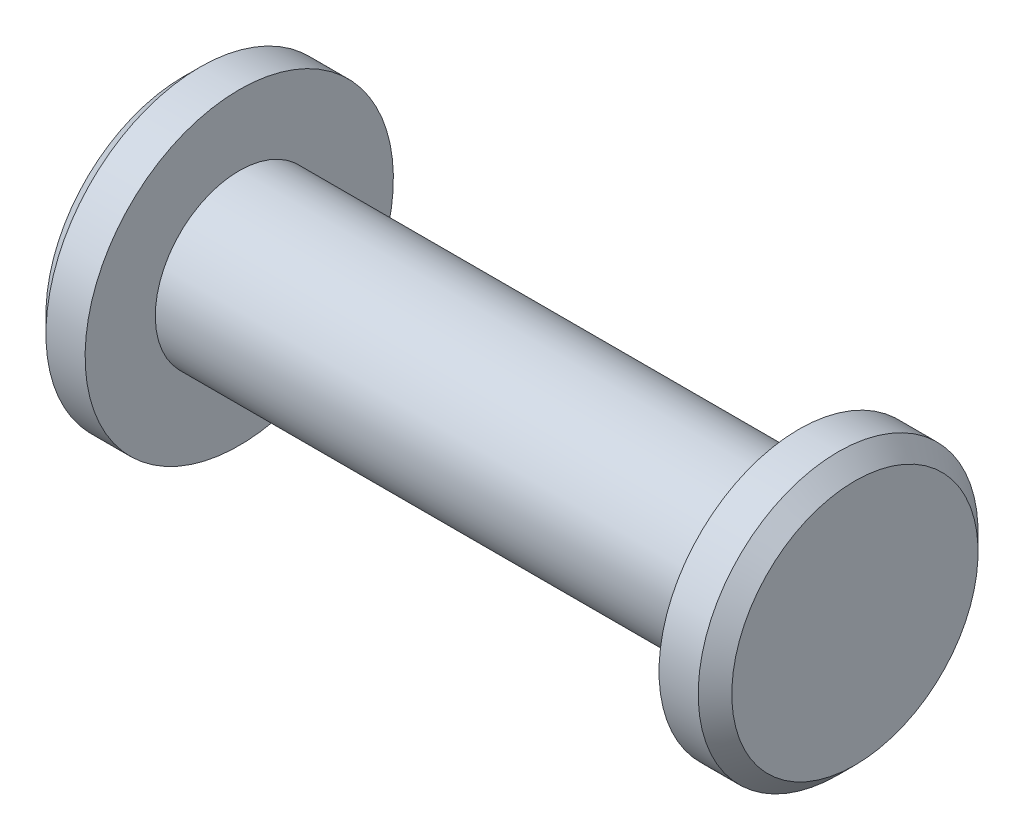
SolidWorks part; units mm, degrees
ref_plane "Front Plane" through (0, 0, 0) normal (0, 0, 1) x (1, 0, 0)
ref_plane "Top Plane" through (0, 0, 0) normal (0, 1, 0) x (1, 0, 0)
ref_plane "Right Plane" through (0, 0, 0) normal (1, 0, 0) x (0, 0, -1)
sketch "Sketch1" plane through (0, 0, 0) normal (0, 0, 1) x (1, 0, 0)
  line L0 (0, 0) -> (-120, 0)
  line L1 (-120, 0) -> (-120, 27.5382)
  line L2 (-120, 27.5382) -> (-110, 27.5382)
  line L3 (-110, 27.5382) -> (-110, 15)
  line L4 (-110, 15) -> (-10, 15)
  line L5 (-10, 15) -> (-10, 25)
  line L6 (-10, 25) -> (0, 25)
  line L7 (0, 25) -> (0, 0)
  dimension "D1" = 100
  dimension "D2" = 10
  dimension "D3" = 10
  dimension "D4" = 25
  dimension "D5" = 15
revolve "Revolve1" add sketch "Sketch1" angle 360 about L0
chamfer "Chamfer1" distance 3 angle 45 2 edges at (-120, 27.5382, 0) (0, 25, 0)
